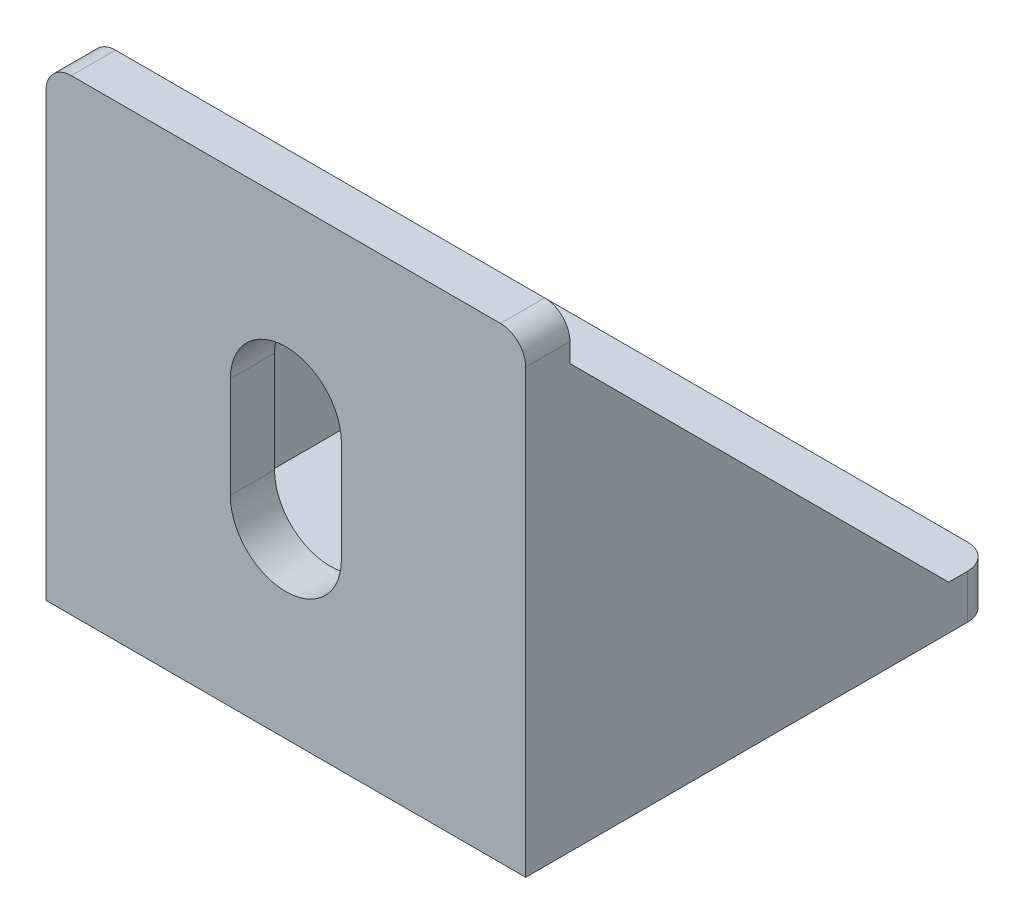
SolidWorks part; units mm, degrees
material "2024 Alaşım"
ref_plane "Ön Düzlem" through (0, 0, 0) normal (0, 0, 1) x (1, 0, 0)
ref_plane "Üst Düzlem" through (0, 0, 0) normal (0, 1, 0) x (1, 0, 0)
ref_plane "Sağ Düzlem" through (0, 0, 0) normal (1, 0, 0) x (0, 0, -1)
sketch "Çizim1" plane through (0, 0, 0) normal (1, 0, 0) x (0, 0, -1)
  line L0 (0, 0) -> (0, 37)
  line L1 (0, 0) -> (37, 0)
  line L2 (33.5, 3.5) -> (37, 3.5)
  line L3 (3.5, 33.5) -> (3.5, 37)
  line L4 (0, 37) -> (3.5, 37)
  line L5 (37, 3.5) -> (37, 0)
  line L6 (3.5, 33.5) -> (33.5, 3.5)
  line L7 (3.5, 3.5) -> (3.5, 37) construction
  line L8 (3.5, 3.5) -> (37, 3.5) construction
  dimension "D1" = 37
  dimension "D2" = 37
  dimension "D4" = 3.5
  dimension "D5" = 3.5
  dimension "D3" = 3.5
extrude "Yükseklik-Ekstrüzyon1" add sketch "Çizim1" along normal blind 38
sketch "Çizim2" plane through (0, 0, -37) normal (0, 0, -1) x (-1, 0, 0)
  line L0 (-34.5, 3.5) -> (-34.5, 33.5)
  line L1 (-38, 3.5) -> (0, 3.5) construction
  line L2 (-38, 33.5) -> (0, 33.5) construction
  line L3 (-34.5, 33.5) -> (-3.5, 33.5)
  line L4 (-3.5, 33.5) -> (-3.5, 3.5)
  line L5 (-3.5, 3.5) -> (-34.5, 3.5)
  line L6 (-38, 3.5) -> (-38, 33.5) construction
  line L7 (0, 3.5) -> (0, 33.5) construction
  dimension "D1" = 3.5
  dimension "D2" = 3.5
extrude "Kes-Ekstrüzyon1" cut sketch "Çizim2" against normal up to surface (33.5 mm away) up to face at (19, 35.25, -3.5)
sketch "Çizim3" plane through (0, 0, -3.5) normal (0, 0, -1) x (-1, 0, 0)
  line L0 (-19, 22.5) -> (-19, 14.5) construction
  line L1 (-14.6, 22.5) -> (-14.6, 14.5)
  line L2 (-23.4, 22.5) -> (-23.4, 14.5)
  line L3 (-38, 37) -> (0, 37) construction
  arc A0 (-14.6, 22.5) -> (-23.4, 22.5) centre (-19, 22.5) ccw
  arc A1 (-23.4, 14.5) -> (-14.6, 14.5) centre (-19, 14.5) ccw
  point P2 (-19, 18.5)
  dimension "D1" = 8
  dimension "D2" = 8.8
  dimension "D3" = 14.5
extrude "Kes-Ekstrüzyon2" cut sketch "Çizim3" against normal blind 38
sketch "Çizim4" plane through (0, 3.5, 0) normal (0, 1, 0) x (1, 0, 0)
  line L1 (38, 37) -> (0, 37) construction
  line L2 (19, 22.5) -> (19, 14.5) construction
  line L3 (23.4, 22.5) -> (23.4, 14.5)
  line L4 (14.6, 22.5) -> (14.6, 14.5)
  arc A0 (23.4, 22.5) -> (14.6, 22.5) centre (19, 22.5) ccw
  arc A1 (14.6, 14.5) -> (23.4, 14.5) centre (19, 14.5) ccw
  point P6 (19, 18.5)
  dimension "D1" = 8
  dimension "D2" = 8.8
  dimension "D3" = 14.5
extrude "Kes-Ekstrüzyon3" cut sketch "Çizim4" against normal blind 38
fillet "Radyus2" radius 2 4 edges at (0, 1.75, -37) (0, 37, -1.75) (38, 37, -1.75) (38, 1.75, -37)
ref_plane "Düzlem1" through (19, 0, 0) normal (1, 0, 0) x (0, 0, -1)
